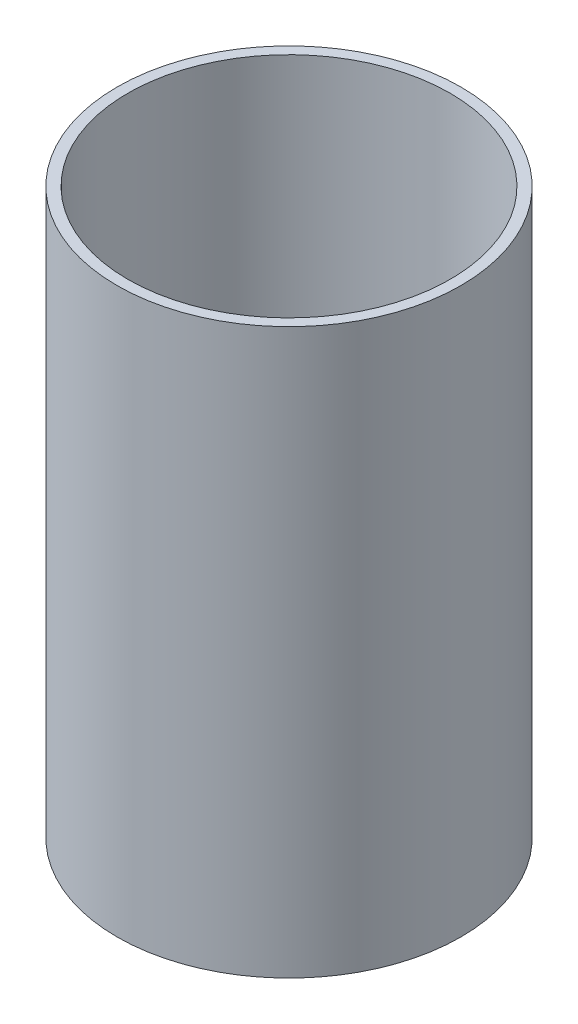
SolidWorks part; units mm, degrees
ref_plane "Front Plane" through (0, 0, 0) normal (0, 0, 1) x (1, 0, 0)
ref_plane "Top Plane" through (0, 0, 0) normal (0, 1, 0) x (1, 0, 0)
ref_plane "Right Plane" through (0, 0, 0) normal (1, 0, 0) x (0, 0, -1)
sketch "Sketch1" plane through (0, 0, 0) normal (0, 1, 0) x (1, 0, 0)
  circle A0 centre (0, 0) radius 0.5715
  circle A1 centre (0, 0) radius 0.6096
extrude "Boss-Extrude1" add sketch "Sketch1" along normal blind 2
